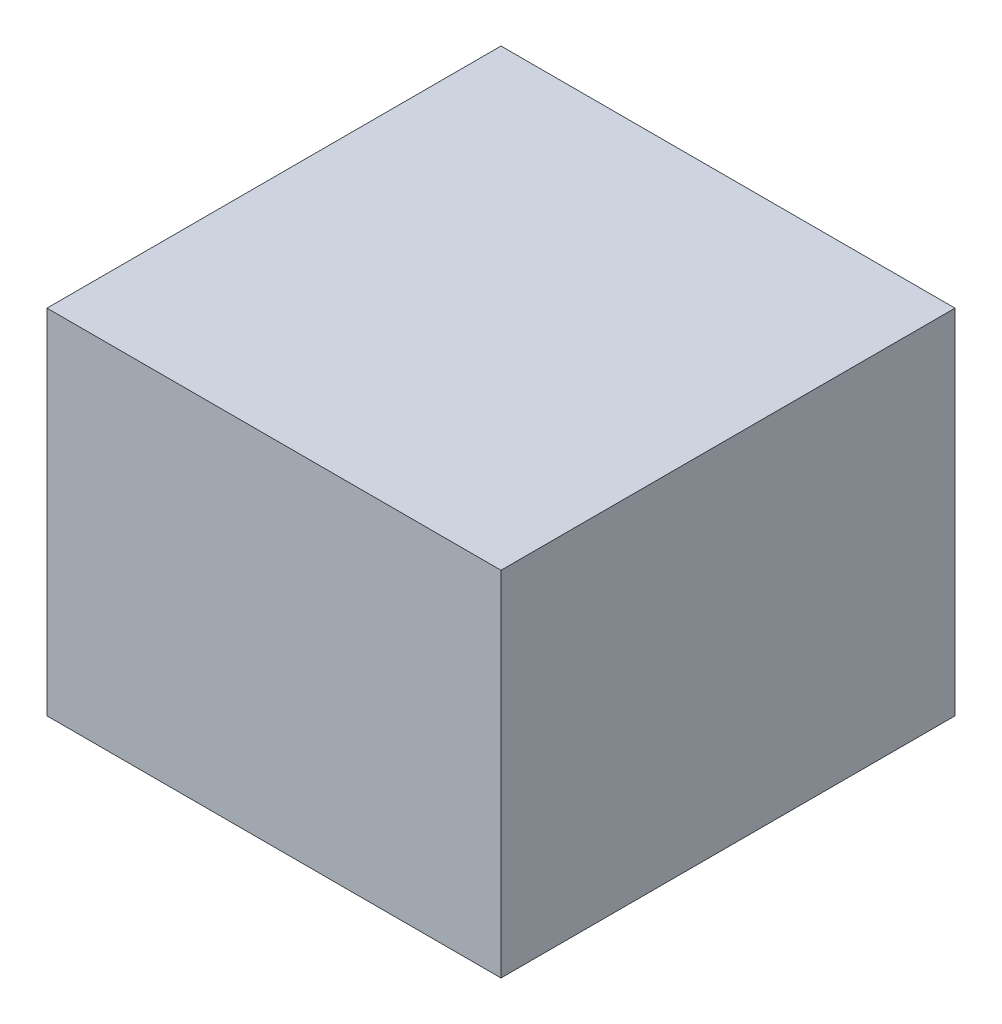
SolidWorks part; units mm, degrees
ref_plane "Front Plane" through (0, 0, 0) normal (0, 0, 1) x (1, 0, 0)
ref_plane "Top Plane" through (0, 0, 0) normal (0, 1, 0) x (1, 0, 0)
ref_plane "Right Plane" through (0, 0, 0) normal (1, 0, 0) x (0, 0, -1)
sketch "Sketch1" plane through (0, 0, 0) normal (0, 1, 0) x (1, 0, 0)
  line L1 (0, 0) -> (57.15, 0)
  line L2 (0, 0) -> (0, 57.15)
  line L3 (0, 57.15) -> (57.15, 57.15)
  line L4 (57.15, 0) -> (57.15, 57.15)
  dimension "D1" = 57.15
  dimension "D2" = 57.15
extrude "Boss-Extrude1" add sketch "Sketch1" along normal blind 44.45
